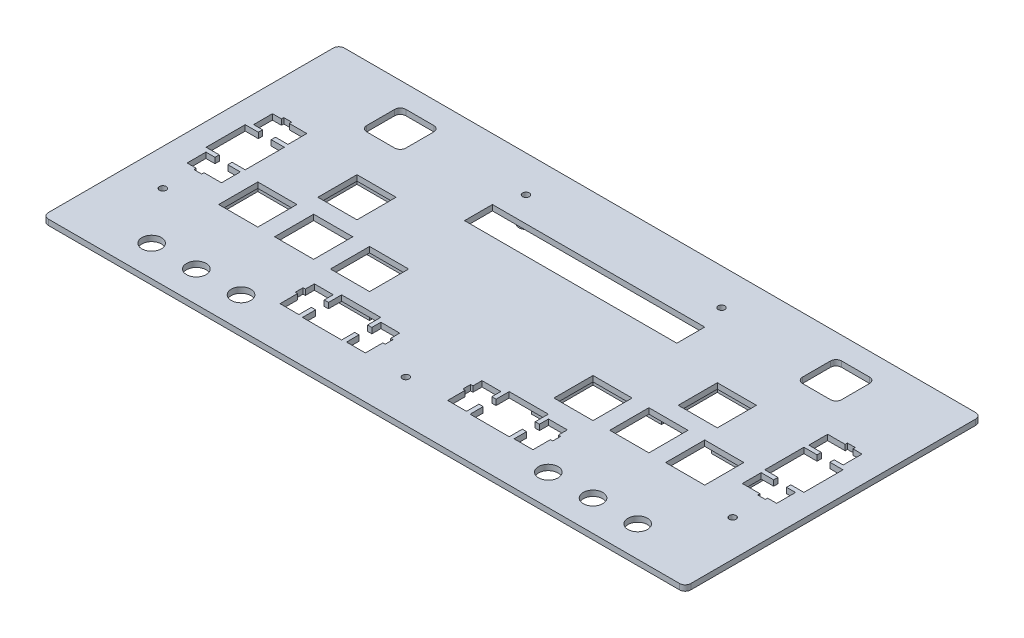
SolidWorks part; units mm, degrees
ref_plane "Front Plane" through (0, 0, 0) normal (0, 0, 1) x (1, 0, 0)
ref_plane "Top Plane" through (0, 0, 0) normal (0, 1, 0) x (1, 0, 0)
ref_plane "Right Plane" through (0, 0, 0) normal (1, 0, 0) x (0, 0, -1)
sketch "Sketch2" plane through (0, 0, 0) normal (0, 1, 0) x (1, 0, 0)
  line L5 (115, -53) -> (-115, -53)
  line L6 (115, -53) -> (115, 53)
  line L7 (115, 53) -> (-115, 53)
  line L8 (-115, -53) -> (-115, 53)
  line L9 (115, -53) -> (-115, 53) construction
  line L10 (115, 53) -> (-115, -53) construction
  point P0 (0, 0)
  dimension "D1" = 230
  dimension "D2" = 106
extrude "Boss-Extrude1" add sketch "Sketch2" along normal blind 2
sketch "PCB_board" plane through (0, 0, 0) normal (0, 1, 0) x (1, 0, 0)
  line L1 (112, -50) -> (-112, -50)
  line L2 (112, -50) -> (112, 50)
  line L3 (112, 50) -> (-112, 50)
  line L4 (-112, -50) -> (-112, 50)
  line L5 (112, -50) -> (-112, 50) construction
  line L6 (112, 50) -> (-112, -50) construction
  point P0 (0, 0)
  dimension "D1" = 224
  dimension "D2" = 100
sketch "S_2.75U_L" plane through (-73.1806, 0, -0.4794) normal (0, 1, 0) x (0, 0, -1)
  line L1 (-2.9794, 33.8194) -> (11.0206, 33.8194) construction
  line L2 (-2.9794, 33.8194) -> (11.0206, 33.8194)
  line L3 (-2.9794, 19.8194) -> (11.0206, 19.8194)
  line L4 (11.0206, 33.8194) -> (11.0206, 29.1194)
  line L5 (11.0206, 19.8194) -> (11.0206, 24.5194)
  line L6 (11.0206, 29.1194) -> (12.5456, 29.1194)
  line L7 (11.0206, 24.5194) -> (12.5456, 24.5194)
  line L8 (12.5456, 29.1194) -> (12.5456, 32.3494)
  line L9 (12.5456, 24.5194) -> (12.5456, 20.0494)
  line L10 (12.5456, 32.3494) -> (19.2956, 32.3494)
  line L11 (19.2956, 32.3494) -> (19.2956, 29.1194)
  line L12 (19.2956, 29.1194) -> (20.1206, 29.1194)
  line L13 (20.1206, 29.1194) -> (20.1206, 26.3194)
  line L14 (20.1206, 26.3194) -> (19.2956, 26.3194)
  line L15 (19.2956, 26.3194) -> (19.2956, 20.0494)
  line L16 (19.2956, 20.0494) -> (12.5456, 20.0494)
  line L17 (-2.9794, 33.8194) -> (-2.9794, 29.1194)
  line L18 (-2.9794, 19.8194) -> (-2.9794, 24.5194)
  line L19 (-2.9794, 29.1194) -> (-4.5044, 29.1194)
  line L20 (-4.5044, 29.1194) -> (-4.5044, 32.3494)
  line L21 (-4.5044, 32.3494) -> (-11.2544, 32.3494)
  line L22 (-11.2544, 32.3494) -> (-11.2544, 29.1194)
  line L23 (-11.2544, 29.1194) -> (-12.0794, 29.1194)
  line L24 (-12.0794, 29.1194) -> (-12.0794, 26.3194)
  line L25 (-12.0794, 26.3194) -> (-11.2544, 26.3194)
  line L26 (-11.2544, 26.3194) -> (-11.2544, 20.0494)
  line L27 (-11.2544, 20.0494) -> (-4.5044, 20.0494)
  line L28 (-4.5044, 20.0494) -> (-4.5044, 24.5194)
  line L29 (-4.5044, 24.5194) -> (-2.9794, 24.5194)
  line L31 (-50.4794, -185.1806) -> (-50.4794, 38.8194) construction
  line L32 (-2.1294, -73.1806) -> (1.1706, -73.1806) construction
  point P5 (4.0206, 33.8194)
  point P34 (4.0206, 26.8194)
  dimension "D1" = 14
  dimension "D2" = 4.7
  dimension "D3" = 4.7
  dimension "D4" = 4.7
  dimension "D5" = 4.7
  dimension "D6" = 4.6
  dimension "D7" = 4.6
  dimension "D8" = 1.525
  dimension "D9" = 1.525
  dimension "D10" = 3.23
  dimension "D11" = 3.23
  dimension "D12" = 6.75
  dimension "D13" = 6.75
  dimension "D14" = 3.23
  dimension "D15" = 0.825
  dimension "D16" = 2.8
  dimension "D17" = 0.825
  dimension "D18" = 6.27
  dimension "D19" = 3.23
  dimension "D20" = 0.825
  dimension "D21" = 2.8
  dimension "D22" = 0.825
  dimension "D23" = 6.27
  dimension "D24" = 6.75
  dimension "D25" = 1.525
  dimension "D26" = 7
  dimension "D27" = 7
  dimension "D28" = 100
  dimension "54.5" = 54.5
sketch "S_2.75U_bot" plane through (0, 0, 0) normal (0, 1, 0) x (1, 0, 0)
  line L0 (-37, -24) -> (-23, -24) construction
  line L1 (-37, -24) -> (-23, -24)
  line L2 (-37, -38) -> (-23, -38)
  line L3 (-23, -24) -> (-23, -28.7)
  line L4 (-23, -38) -> (-23, -33.3)
  line L5 (-23, -28.7) -> (-21.475, -28.7)
  line L6 (-23, -33.3) -> (-21.475, -33.3)
  line L7 (-21.475, -28.7) -> (-21.475, -25.47)
  line L8 (-21.475, -33.3) -> (-21.475, -37.77)
  line L9 (-21.475, -25.47) -> (-14.725, -25.47)
  line L10 (-14.725, -25.47) -> (-14.725, -28.7)
  line L11 (-14.725, -28.7) -> (-13.9, -28.7)
  line L12 (-13.9, -28.7) -> (-13.9, -31.5)
  line L13 (-13.9, -31.5) -> (-14.725, -31.5)
  line L14 (-14.725, -31.5) -> (-14.725, -37.77)
  line L15 (-14.725, -37.77) -> (-21.475, -37.77)
  line L16 (-37, -24) -> (-37, -28.7)
  line L17 (-37, -38) -> (-37, -33.3)
  line L18 (-37, -28.7) -> (-38.525, -28.7)
  line L19 (-38.525, -28.7) -> (-38.525, -25.47)
  line L20 (-38.525, -25.47) -> (-45.275, -25.47)
  line L21 (-45.275, -25.47) -> (-45.275, -28.7)
  line L22 (-45.275, -28.7) -> (-46.1, -28.7)
  line L23 (-46.1, -28.7) -> (-46.1, -31.5)
  line L24 (-46.1, -31.5) -> (-45.275, -31.5)
  line L25 (-45.275, -31.5) -> (-45.275, -37.77)
  line L26 (-45.275, -37.77) -> (-38.525, -37.77)
  line L27 (-38.525, -37.77) -> (-38.525, -33.3)
  line L28 (-38.525, -33.3) -> (-37, -33.3)
  line L29 (112, -50) -> (-112, -50) construction
  line L30 (0, -1.65) -> (0, 1.65) construction
  point P3 (-30, -24)
  point P31 (-30, -31)
  dimension "D1" = 14
  dimension "D2" = 4.7
  dimension "D3" = 4.7
  dimension "D4" = 4.7
  dimension "D5" = 4.7
  dimension "D6" = 4.6
  dimension "D7" = 4.6
  dimension "D8" = 1.525
  dimension "D9" = 1.525
  dimension "D10" = 3.23
  dimension "D11" = 3.23
  dimension "D12" = 6.75
  dimension "D13" = 6.75
  dimension "D14" = 3.23
  dimension "D15" = 0.825
  dimension "D16" = 2.8
  dimension "D17" = 0.825
  dimension "D18" = 6.27
  dimension "D19" = 3.23
  dimension "D20" = 0.825
  dimension "D21" = 2.8
  dimension "D22" = 0.825
  dimension "D23" = 6.27
  dimension "D24" = 6.75
  dimension "D25" = 1.525
  dimension "D26" = 7
  dimension "D27" = 7
  dimension "D28" = 19
  dimension "D29" = 30
sketch "S_1U_L" plane through (0, 0, 0) normal (0, 1, 0) x (1, 0, 0)
  line L0 (0, -1.65) -> (0, 1.65) construction
  line L1 (-47, -18) -> (-33, -18)
  line L2 (-47, -18) -> (-47, -4)
  line L3 (-47, -4) -> (-33, -4)
  line L4 (-33, -18) -> (-33, -4)
  line L5 (-47, -18) -> (-33, -4) construction
  line L6 (-47, -4) -> (-33, -18) construction
  line L8 (-67, -18) -> (-53, -18)
  line L9 (-67, -18) -> (-67, -4)
  line L10 (-67, -4) -> (-53, -4)
  line L11 (-53, -18) -> (-53, -4)
  line L12 (-67, -18) -> (-53, -4) construction
  line L13 (-67, -4) -> (-53, -18) construction
  line L18 (-73, -18) -> (-87, -18)
  line L19 (-73, -18) -> (-73, -4)
  line L20 (-73, -4) -> (-87, -4)
  line L21 (-87, -18) -> (-87, -4)
  line L22 (-73, -18) -> (-87, -4) construction
  line L23 (-73, -4) -> (-87, -18) construction
  line L24 (-57.5, 2) -> (-71.5, 2)
  line L25 (-57.5, 2) -> (-57.5, 16)
  line L26 (-57.5, 16) -> (-71.5, 16)
  line L27 (-71.5, 2) -> (-71.5, 16)
  line L28 (-57.5, 2) -> (-71.5, 16) construction
  line L29 (-57.5, 16) -> (-71.5, 2) construction
  point P0 (-40, -11)
  point P8 (-60, -11)
  point P13 (-80, -11)
  point P17 (-64.5, 9)
  dimension "D1" = 40
  dimension "D2" = 14
  dimension "D3" = 14
  dimension "D4" = 20
  dimension "D5" = 20
  dimension "D6" = 14
  dimension "D7" = 20
  dimension "D8" = 14
  dimension "D9" = 4.5
  dimension "D10" = 20
sketch "Sketch4" plane through (0, 0, 0) normal (0, 1, 0) x (1, 0, 0)
  line L0 (0, -1.65) -> (0, 1.65) construction
  line L1 (-38, 31) -> (38, 31)
  line L2 (-38, 31) -> (-38, 21)
  line L3 (-38, 21) -> (38, 21)
  line L4 (38, 31) -> (38, 21)
  line L7 (-57.5, 16) -> (-71.5, 16) construction
  dimension "D1" = 76
  dimension "D2" = 10
  dimension "D3" = 38
  dimension "D4" = 5
extrude "2.75U keyswitch_L" cut sketch "S_2.75U_L" along normal through all
extrude "2.75U keyswitch_bot" cut sketch "S_2.75U_bot" along normal through all
extrude "1U keyswitchs_L" cut sketch "S_1U_L" along normal through all
mirror "Mirror1" about plane through (0, 0, 0) normal (1, 0, 0) of "1U keyswitchs_L", "2.75U keyswitch_bot", "2.75U keyswitch_L"
extrude "potentiometer slider" cut sketch "Sketch4" along normal through all
sketch "Sketch37" plane through (0, 0, 0) normal (0, 1, 0) x (1, 0, 0)
  line L0 (-85, 45) -> (-71, 31) construction
  line L1 (-85, 45) -> (-71, 45)
  line L2 (-85, 45) -> (-85, 31)
  line L3 (-85, 31) -> (-71, 31)
  line L4 (-71, 45) -> (-71, 31)
  line L5 (-71, 45) -> (-85, 31) construction
  line L6 (112, 50) -> (-112, 50) construction
  line L7 (-112, -50) -> (-112, 50) construction
  point P4 (-78, 38)
  dimension "D1" = 14
  dimension "D2" = 12
  dimension "D3" = 34
extrude "Cut-Extrude1" cut sketch "Sketch37" along normal through all
fillet "Fillet2" radius 2 4 edges at (-71, 1, -31) (-85, 1, -31) (-71, 1, -45) (-85, 1, -45)
mirror "Mirror7" about plane through (0, 0, 0) normal (1, 0, 0) of "Cut-Extrude1", "Fillet2"
fillet "Fillet1" radius 2 4 edges at (-115, 1, -53) (-115, 1, 53) (115, 1, 53) (115, 1, -53)
sketch "Sketch8" plane through (0, 0, 0) normal (0, 1, 0) x (1, 0, 0)
  line L0 (0, -1.1) -> (0, 1.1) construction
  line L2 (-113, -53) -> (113, -53) construction
  circle A1 centre (0, -38) radius 2.5
  dimension "D1" = 5
  dimension "D3" = 15
extrude "anchor_cylinder_botA" add sketch "Sketch8" against normal blind 7
sketch "Sketch24" plane through (0, 0, 0) normal (0, 1, 0) x (1, 0, 0)
  circle A0 centre (0, -38) radius 5
  dimension "D1" = 10
extrude "anchor_cylinder_botB" add sketch "Sketch24" against normal blind 3
sketch "Sketch16" plane through (0, 2, 0) normal (0, 1, 0) x (1, 0, 0)
  circle A1 centre (0, -38) radius 2.5 construction
  point P4 (0, -38)
hole_wizard "anchor_hole_bot" positions "Sketch16" profile "Sketch15" hole size "M2" standard "ANSI Metric" end condition through all
sketch "Sketch15" plane through (0, 2, 38) normal (1, 0, 0) x (0, 0, 1)
  line L0 (0, 0) -> (0, 9)
  line L1 (0, 9) -> (1.2, 9)
  line L2 (1.2, 9) -> (1.2, 0)
  line L5 (1.2, 0) -> (0, 0)
  line L11 (0, -6.35) -> (0, 107.95) construction
  dimension "Thru Hole Dia." = 2.4
  dimension "Thru Hole Depth" = 9
sketch "Sketch17" plane through (0, 0, 0) normal (0, 1, 0) x (1, 0, 0)
  line L5 (53.5, 20) -> (53.5, 0)
  line L10 (53.5, 0) -> (29, 0)
  line L11 (29, 0) -> (29, -22)
  line L12 (29, -22) -> (91, -22)
  line L13 (91, -22) -> (91, 0)
  line L14 (91, 0) -> (75.5, 0)
  line L15 (75.5, 0) -> (75.5, 20)
  line L16 (75.5, 20) -> (53.5, 20)
  line L17 (33, -4) -> (47, -4) construction
  line L18 (47, -18) -> (33, -18) construction
  line L19 (33, -18) -> (33, -4) construction
  line L20 (87, -4) -> (87, -18) construction
  line L21 (57.5, 2) -> (57.5, 16) construction
  line L22 (71.5, 16) -> (71.5, 2) construction
  line L23 (57.5, 16) -> (71.5, 16) construction
  dimension "D1" = 4
  dimension "D2" = 4
  dimension "D3" = 4
  dimension "D4" = 4
  dimension "D5" = 4
  dimension "D6" = 4
  dimension "D7" = 4
extrude "Boss-keySw_Sup_L" add sketch "Sketch17" against normal blind 3
sketch "Sketch18" plane through (0, 0, 0) normal (0, 1, 0) x (1, 0, 0)
  line L0 (55.5, 18) -> (55.5, -2)
  line L1 (55.5, -2) -> (31, -2)
  line L2 (31, -2) -> (31, -20)
  line L3 (31, -20) -> (89, -20)
  line L4 (89, -20) -> (89, -2)
  line L5 (89, -2) -> (73.5, -2)
  line L6 (73.5, -2) -> (73.5, 18)
  line L7 (73.5, 18) -> (55.5, 18)
  line L8 (57.5, 16) -> (71.5, 16) construction
  line L9 (71.5, 16) -> (71.5, 2) construction
  line L10 (57.5, 2) -> (57.5, 16) construction
  line L11 (33, -4) -> (47, -4) construction
  line L12 (33, -18) -> (33, -4) construction
  line L13 (47, -18) -> (33, -18) construction
  line L14 (73, -4) -> (87, -4) construction
  line L15 (87, -4) -> (87, -18) construction
  dimension "D1" = 2
  dimension "D2" = 2
  dimension "D3" = 2
  dimension "D4" = 2
  dimension "D5" = 2
  dimension "D6" = 2
  dimension "D7" = 2
  dimension "D8" = 2
extrude "Cut-keySw_Sup_L" cut sketch "Sketch18" against normal blind 3
mirror "Mirror3" about plane through (0, 0, 0) normal (1, 0, 0) of "Cut-keySw_Sup_L", "Boss-keySw_Sup_L"
sketch "Sketch19" plane through (0, 0, 0) normal (0, 1, 0) x (1, 0, 0)
  line L0 (113, 53) -> (-113, 53) construction
  line L1 (0, -1.1) -> (0, 1.1) construction
  line L2 (112, 50) -> (-112, 50) construction
  circle A0 centre (-35, 40) radius 2.5
  dimension "D2" = 5
  dimension "D1" = 13
  dimension "D3" = 35
  dimension "D4" = 10
extrude "anchor_cylinder_TLA" add sketch "Sketch19" against normal blind 7
sketch "Sketch26" plane through (0, 0, 0) normal (0, 1, 0) x (1, 0, 0)
  circle A0 centre (-35, 40) radius 5
  dimension "D1" = 10
extrude "anchor_cylinder_TLB" add sketch "Sketch26" against normal blind 3
sketch "Sketch29" plane through (0, -7, 0) normal (0, -1, 0) x (-1, 0, 0)
  point P0 (35, 40)
hole_wizard "anchor_hole_TL" positions "Sketch29" profile "Sketch28" hole size "M2" standard "ANSI Metric" end condition through all
sketch "Sketch28" plane through (-35, -7, -40) normal (1, 0, 0) x (0, 0, -1)
  line L0 (0, 0) -> (0, 9)
  line L1 (0, 9) -> (1.2, 9)
  line L2 (1.2, 9) -> (1.2, 0)
  line L5 (1.2, 0) -> (0, 0)
  line L11 (0, -6.35) -> (0, 107.95) construction
  dimension "Thru Hole Dia." = 2.4
  dimension "Thru Hole Depth" = 9
sketch "Sketch23" plane through (0, 0, 0) normal (0, 1, 0) x (1, 0, 0)
  line L1 (-93.275, -26) -> (-53.275, -26)
  line L2 (-93.275, -26) -> (-93.275, -41)
  line L3 (-93.275, -41) -> (-53.275, -41)
  line L4 (-53.275, -26) -> (-53.275, -41)
  line L7 (-45.275, -31.5) -> (-45.275, -37.77) construction
  line L9 (-113, -53) -> (113, -53) construction
  dimension "D1" = 8
  dimension "D2" = 12
  dimension "D3" = 40
  dimension "D4" = 15
extrude "small_button_space" [suppressed] cut sketch "Sketch23" along normal through all
mirror "Mirror4" about plane through (0, 0, 0) normal (1, 0, 0) of "anchor_cylinder_TLB", "anchor_hole_TL", "anchor_cylinder_TLA"
sketch "Sketch30" plane through (0, 0, 0) normal (0, 1, 0) x (1, 0, 0)
  circle A0 centre (0, 0) radius 4
  circle A1 centre (0, 0) radius 2.5
  dimension "D1" = 5
  dimension "D2" = 8
extrude "Boss-Extrude5" add sketch "Sketch30" against normal blind 3
sketch "Sketch31" plane through (0, 0, 0) normal (0, 1, 0) x (1, 0, 0)
  line L0 (-112, -50) -> (-112, 50) construction
  line L1 (112, -50) -> (-112, -50) construction
  circle A0 centre (-102, -23) radius 5
  dimension "D1" = 10
  dimension "D2" = 10
  dimension "D3" = 27
extrude "anchor_cylinder_BLB" add sketch "Sketch31" against normal blind 3
sketch "Sketch32" plane through (0, 0, 0) normal (0, 1, 0) x (1, 0, 0)
  circle A0 centre (-102, -23) radius 2.5
  dimension "D1" = 5
extrude "anchor_cylinder_BLA" add sketch "Sketch32" against normal blind 7
sketch "Sketch35" plane through (0, -7, 0) normal (0, -1, 0) x (-1, 0, 0)
  point P0 (102, -23)
hole_wizard "anchor_hole_BL" positions "Sketch35" profile "Sketch34" hole size "M2" standard "ANSI Metric" end condition through all
sketch "Sketch34" plane through (-102, -7, 23) normal (1, 0, 0) x (0, 0, -1)
  line L0 (0, 0) -> (0, 9)
  line L1 (0, 9) -> (1.2, 9)
  line L2 (1.2, 9) -> (1.2, 0)
  line L5 (1.2, 0) -> (0, 0)
  line L11 (0, -6.35) -> (0, 107.95) construction
  dimension "Thru Hole Dia." = 2.4
  dimension "Thru Hole Depth" = 9
mirror "Mirror5" about plane through (0, 0, 0) normal (1, 0, 0) of "anchor_hole_BL", "anchor_cylinder_BLA", "anchor_cylinder_BLB"
sketch "Sketch36" plane through (0, 0, 0) normal (0, 1, 0) x (1, 0, 0)
  line L2 (-1.1, 0) -> (1.1, 0) construction
  line L3 (-47, -4) -> (-47, -18) construction
  circle A0 centre (-55, -42) radius 3.5
  dimension "D1" = 7
  dimension "42" = 42
  dimension "D3" = 8
extrude "SW_hole" cut sketch "Sketch36" along normal through all
pattern_linear "LPattern1" count 3 spacing 16 along (-1, 0, 0) of "SW_hole"
mirror "Mirror6" about plane through (0, 0, 0) normal (1, 0, 0) of "SW_hole", "LPattern1"
sketch "Sketch38" plane through (0, 0, 0) normal (0, 1, 0) x (1, 0, 0)
  line L0 (-103.5, 43) -> (-98.5, 39) construction
  line L1 (-103.5, 43) -> (-98.5, 43)
  line L2 (-103.5, 43) -> (-103.5, 39)
  line L3 (-103.5, 39) -> (-98.5, 39)
  line L4 (-98.5, 43) -> (-98.5, 39)
  line L5 (-98.5, 43) -> (-103.5, 39) construction
  line L10 (113, 53) -> (-113, 53) construction
  line L11 (-115, 51) -> (-115, -51) construction
  point P6 (-101, 41)
  dimension "D1" = 4
  dimension "D2" = 5
  dimension "D3" = 12
  dimension "D4" = 14
